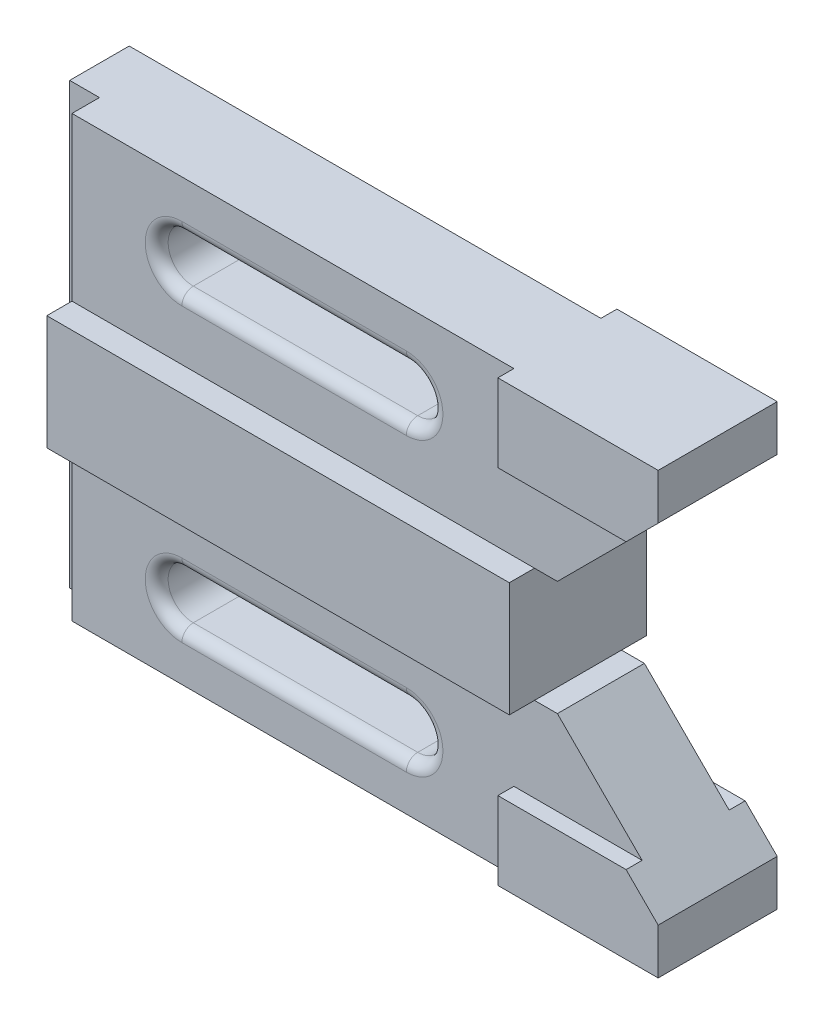
SolidWorks part; units mm, degrees
material "1060 合金"
ref_plane "前视基准面" through (0, 0, 0) normal (0, 0, 1) x (1, 0, 0)
ref_plane "上视基准面" through (0, 0, 0) normal (0, 1, 0) x (1, 0, 0)
ref_plane "右视基准面" through (0, 0, 0) normal (1, 0, 0) x (0, 0, -1)
sketch "草图1" plane through (0, 0, 0) normal (0, 0, 1) x (1, 0, 0)
  line L0 (-117.1075, 0) -> (144.4691, 0) construction
  line L1 (0, 78.8795) -> (0, -83.7264) construction
  line L3 (-107.5, 48) -> (30.5, 48)
  line L4 (30.5, 48) -> (30.5, 38)
  line L5 (30.5, 38) -> (5, 12.5)
  line L6 (5, 12.5) -> (0, 12.5)
  line L7 (0, 12.5) -> (0, -12.5)
  line L8 (0, -12.5) -> (5, -12.5)
  line L9 (5, -12.5) -> (30.5, -38)
  line L10 (30.5, -38) -> (30.5, -48)
  line L11 (30.5, -48) -> (-107.5, -48)
  line L13 (-107.5, 48) -> (-107.5, -48)
  line L14 (0, 12.5) -> (-107.5, 12.5)
  line L15 (0, -12.5) -> (-107.5, -12.5)
  line L16 (-107.5, 12.5) -> (0, 12.5)
  line L17 (0, -12.5) -> (-107.5, -12.5)
  point P7 (0, 0)
  dimension "D1" = 96
  dimension "D2" = 138
  dimension "D3" = 10
  dimension "D4" = 35.5
  dimension "D5" = 30.5
  dimension "D6" = 10
  dimension "D7" = 35.5
  dimension "D8" = 138
  dimension "D9" = 45
  dimension "D10" = 45
extrude "凸台-拉伸1" add sketch "草图1" along normal mid plane 19 contours L13 L11 L10 L9 L8 L7 L6 L5 L4 L3
sketch "草图2" plane through (0, 0, 9.5) normal (0, 0, 1) x (1, 0, 0)
  line L0 (0, 12.5) -> (-107.5, 12.5)
  line L1 (0, -12.5) -> (-107.5, -12.5)
  line L2 (-4.5, -48) -> (-4.5, -31)
  line L3 (-4.5, -31) -> (23.5, -31)
  line L4 (-4.5, 48) -> (-4.5, 31)
  line L5 (-4.5, 31) -> (23.5, 31)
  line L10 (30.5, 48) -> (-107.5, 48)
  line L11 (-107.5, 48) -> (-107.5, -48)
  line L12 (-107.5, -48) -> (30.5, -48)
  line L13 (30.5, -48) -> (30.5, -38)
  line L14 (30.5, -38) -> (5, -12.5)
  line L15 (5, -12.5) -> (0, -12.5)
  line L16 (0, -12.5) -> (0, 12.5)
  line L17 (0, 12.5) -> (5, 12.5)
  line L18 (5, 12.5) -> (30.5, 38)
  line L19 (30.5, 38) -> (30.5, 48)
  line L20 (30.5, 48) -> (-107.5, 48)
  line L21 (-107.5, 48) -> (-107.5, -48)
  line L22 (-107.5, -48) -> (30.5, -48)
  line L23 (30.5, -48) -> (30.5, -38)
  line L24 (30.5, -38) -> (5, -12.5)
  line L25 (5, -12.5) -> (0, -12.5)
  line L26 (0, -12.5) -> (0, 12.5)
  line L27 (0, 12.5) -> (5, 12.5)
  line L28 (5, 12.5) -> (30.5, 38)
  line L29 (30.5, 38) -> (30.5, 48)
  line M11 (30.5, 48) -> (-107.5, 48)
  line M13 (-107.5, -48) -> (30.5, -48)
  line M14 (30.5, -48) -> (30.5, -38)
  line M15 (30.5, -38) -> (5, -12.5)
  line M19 (5, 12.5) -> (30.5, 38)
  line M20 (30.5, 38) -> (30.5, 48)
  dimension "D2" = 35
  dimension "D3" = 17
  dimension "D4" = 17
  dimension "D1" = 0
extrude "凸台-拉伸2" add sketch "草图2" along normal blind 3.5 and the other way blind 22.5 contours L4 L5 M19 M20 M11 | L3 L2 M13 M14 M15
sketch "草图8" plane through (0, 0, -9.5) normal (0, 0, -1) x (-1, 0, 0)
  line L0 (0, 12.5) -> (0, -12.5)
  line L1 (0, -12.5) -> (107.5, -12.5)
  line L2 (107.5, 48) -> (107.5, -48) construction
  line L3 (107.5, -12.5) -> (107.5, 12.5)
  line L4 (107.5, 12.5) -> (0, 12.5)
extrude "凸台-拉伸3" add sketch "草图8" along normal blind 5.5 and the other way blind 24.5
sketch "草图9" plane through (0, 0, 15) normal (0, 0, 1) x (1, 0, 0)
  line L0 (-107.5, 48) -> (-107.5, -48)
  line L1 (-107.5, -48) -> (-101, -48)
  line L2 (-4.5, -48) -> (-107.5, -48) construction
  line L3 (-101, -48) -> (-101, 48)
  line L4 (-107.5, 48) -> (-4.5, 48) construction
  line L5 (-101, 48) -> (-107.5, 48)
  dimension "D1" = 6.5
extrude "切除-拉伸1" cut sketch "草图9" against normal blind 11.5
sketch "草图11" plane through (0, 0, -9.5) normal (0, 0, -1) x (-1, 0, 0)
  line L0 (28, 31.5901) -> (77, 31.5901) construction
  line L1 (28, 37.0901) -> (77, 37.0901)
  line L2 (28, 26.0901) -> (77, 26.0901)
  line L3 (28, -32.0709) -> (77, -32.0709) construction
  line L4 (28, -26.5709) -> (77, -26.5709)
  line L5 (28, -37.5709) -> (77, -37.5709)
  line L6 (107.5, -12.5) -> (107.5, -48) construction
  line L7 (107.5, 48) -> (107.5, 12.5) construction
  arc A0 (28, 37.0901) -> (28, 26.0901) centre (28, 31.5901) ccw
  arc A1 (77, 26.0901) -> (77, 37.0901) centre (77, 31.5901) ccw
  arc A2 (28, -26.5709) -> (28, -37.5709) centre (28, -32.0709) ccw
  arc A3 (77, -37.5709) -> (77, -26.5709) centre (77, -32.0709) ccw
  point P2 (52.5, 31.5901)
  point P7 (52.5, -32.0709)
  dimension "D4" = 5.5
  dimension "D1" = 49
  dimension "D2" = 30.5
  dimension "D3" = 30.5
extrude "切除-拉伸2" cut sketch "草图11" against normal blind 52.5
fillet "圆角1" radius 2.5 16 edges at (-52.5, 37.0901, 9.5) (-82.5, 31.5901, 9.5) (-52.5, 26.0901, 9.5) (-52.5, 37.0901, -9.5) (-82.5, 31.5901, -9.5) (-52.5, 26.0901, -9.5) (-52.5, -26.5709, 9.5) (-82.5, -32.0709, 9.5) (-52.5, -37.5709, 9.5) (-52.5, -26.5709, -9.5) (-82.5, -32.0709, -9.5) (-52.5, -37.5709, -9.5) (-22.5, 31.5901, 9.5) (-22.5, 31.5901, -9.5) (-22.5, -32.0709, 9.5) (-22.5, -32.0709, -9.5)
